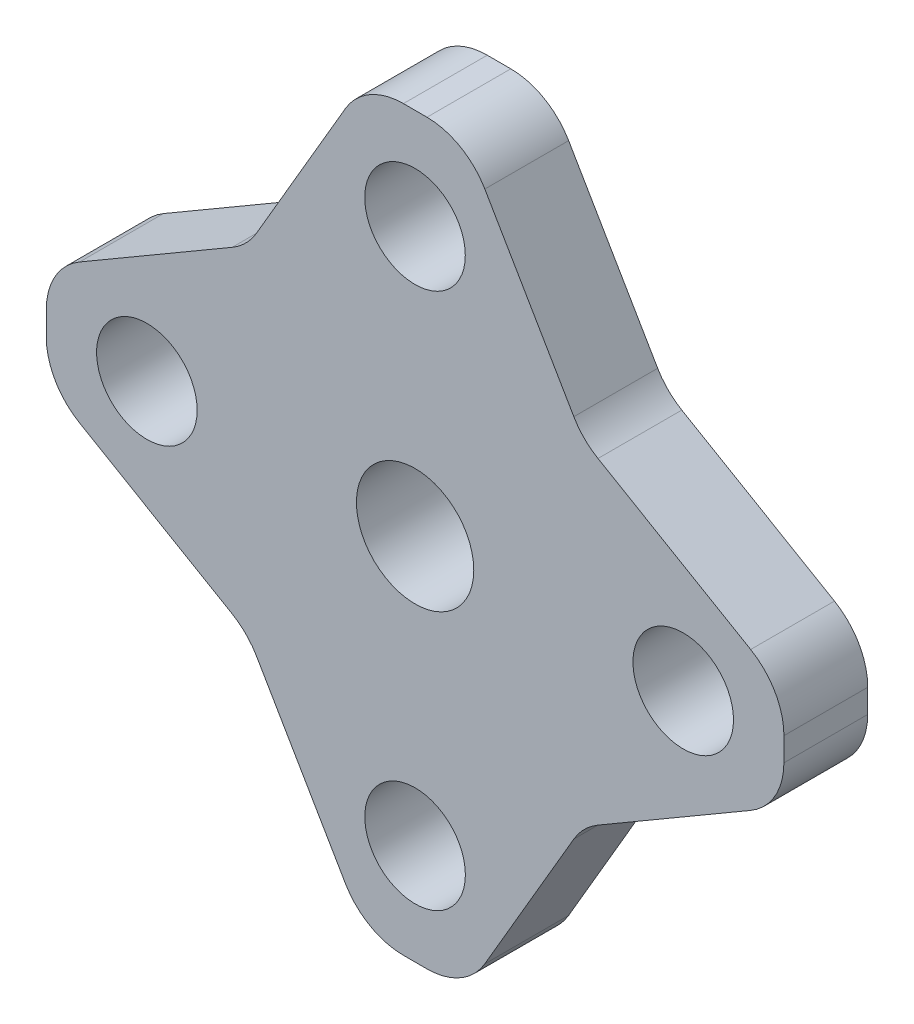
SolidWorks part; units mm, degrees
material "Thornel Mat VMA"
ref_plane "Front Plane" through (0, 0, 0) normal (0, 0, 1) x (1, 0, 0)
ref_plane "Top Plane" through (0, 0, 0) normal (0, 1, 0) x (1, 0, 0)
ref_plane "Right Plane" through (0, 0, 0) normal (1, 0, 0) x (0, 0, -1)
sketch "Sketch1" plane through (0, 0, 0) normal (0, 0, 1) x (1, 0, 0)
  line L0 (0, 14.8318) -> (0, -14.8318)
  line L1 (-5, 14.8318) -> (-5, -14.8318)
  line L2 (5, 14.8318) -> (5, -14.8318)
  line L3 (-12.5, 0) -> (0, -12.5)
  line L4 (-12.5, 0) -> (0, 12.5)
  line L5 (0, -12.5) -> (12.5, 0)
  line L6 (0, 12.5) -> (12.5, 0)
  line L7 (-12.5, 0) -> (12.5, 0) construction
  line L8 (0, -12.5) -> (0, 12.5) construction
  line L9 (-10.9858, 11.0142) -> (11.0142, 10.9858)
  line L10 (-10.9858, 11.0142) -> (-11.0142, -10.9858)
  line L11 (11.0142, 10.9858) -> (10.9858, -11.0142)
  line L12 (-11.0142, -10.9858) -> (10.9858, -11.0142)
  line L13 (-10.9858, 11.0142) -> (10.9858, -11.0142) construction
  line L14 (11.0142, 10.9858) -> (-11.0142, -10.9858) construction
  circle A0 centre (0, 0) radius 8
  circle A1 centre (-8, 0) radius 1.5
  circle A2 centre (-0.0028, 8) radius 1.5
  circle A3 centre (7.9972, 0.0028) radius 1.5
  circle A4 centre (0, -7.9972) radius 1.5
  point P14 (-0.0014, 0.0014)
  point P15 (0, 0)
  dimension "D2" = 3
  dimension "D3" = 16
  dimension "D6" = 25
  dimension "D7" = 22
  dimension "D4" = 5
  dimension "D5" = 5
  dimension "D1" = 4
extrude "Boss-Extrude1" add sketch "Sketch1" along normal blind 2.5 contours A1 A0 L1 L4 L10 L3 | A2 L0 L9 L4 L1 A0 | A2 A0 L2 L6 L9 L0 | A3 A0 L2 L5 L11 L6 | A4 A0 L1 L3 L12 L0 | A4 L0 L12 L5 L2 A0 | A4 L0 A2 A0 L1 | A1 A0 L1 | A4 A0 L2 A2 L0 | A3 A0 L2
sketch "Sketch2" plane through (0, 0, 2.5) normal (0, 0, 1) x (1, 0, 0)
  line L4 (-5, -5) -> (5, 5) construction
  line L5 (5, -5) -> (-5, 5) construction
  line L6 (-5, 5) -> (-10.9981, 1.5019)
  line L7 (-5, -5) -> (5, -5)
  line L8 (-5, -5) -> (-5, 5)
  line L9 (-5, 5) -> (5, 5)
  line L10 (5, -5) -> (5, 5)
  line L11 (-5, -5) -> (5, 5) construction
  line L12 (-5, 5) -> (5, -5) construction
  line L13 (-5, 5) -> (-1.498, 11.002)
  line L14 (-1.498, 11.002) -> (1.5019, 10.9981)
  line L15 (1.5019, 10.9981) -> (5, 5)
  line L16 (5, 5) -> (11.002, 1.498)
  line L17 (-11.002, -1.498) -> (-5, -5)
  line L18 (-5, -5) -> (-1.5019, -10.9981)
  line L19 (1.498, -11.002) -> (5, -5)
  line L20 (10.9981, -1.5019) -> (5, -5)
  line L25 (1.498, -11.002) -> (10.9981, -1.5019)
  line L26 (10.9981, -1.5019) -> (11.002, 1.498)
  line L27 (11.002, 1.498) -> (1.5019, 10.9981)
  line L28 (1.5019, 10.9981) -> (-1.498, 11.002)
  line L29 (-1.498, 11.002) -> (-10.9981, 1.5019)
  line L30 (-10.9981, 1.5019) -> (-11.002, -1.498)
  line L31 (-11.002, -1.498) -> (-1.5019, -10.9981)
  line L32 (-1.5019, -10.9981) -> (1.498, -11.002)
  line L33 (1.498, -11.002) -> (10.9981, -1.5019)
  line L34 (10.9981, -1.5019) -> (11.002, 1.498)
  line L35 (11.002, 1.498) -> (1.5019, 10.9981)
  line L36 (1.5019, 10.9981) -> (-1.498, 11.002)
  line L37 (-1.498, 11.002) -> (-10.9981, 1.5019)
  line L38 (-10.9981, 1.5019) -> (-11.002, -1.498)
  line L39 (-11.002, -1.498) -> (-1.5019, -10.9981)
  line L40 (-1.5019, -10.9981) -> (1.498, -11.002)
  point P0 (0, 0)
  line M18 (1.498, -11.002) -> (10.9981, -1.5019)
  line M20 (11.002, 1.498) -> (1.5019, 10.9981)
  line M22 (-1.498, 11.002) -> (-10.9981, 1.5019)
  line M24 (-11.002, -1.498) -> (-1.5019, -10.9981)
  dimension "D1" = 10
  dimension "D2" = 0
extrude "Cut-Extrude1" cut sketch "Sketch2" against normal blind 2.5 contours L6 L13 M22 | L18 L17 M24 | L15 L16 M20 | L20 L19 M18
sketch "Sketch3" plane through (0, 0, 2.5) normal (0, 0, 1) x (1, 0, 0)
  circle A0 centre (0, 0) radius 1.75
  dimension "D1" = 3.5
extrude "Cut-Extrude2" cut sketch "Sketch3" against normal blind 2.5
fillet "Fillet1" radius 2 12 edges at (-10.9981, 1.5019, 1.25) (-5, 5, 1.25) (-1.498, 11.002, 1.25) (1.5019, 10.9981, 1.25) (5, 5, 1.25) (11.002, 1.498, 1.25) (10.9981, -1.5019, 1.25) (5, -5, 1.25) (1.498, -11.002, 1.25) (-1.5019, -10.9981, 1.25) (-5, -5, 1.25) (-11.002, -1.498, 1.25)
